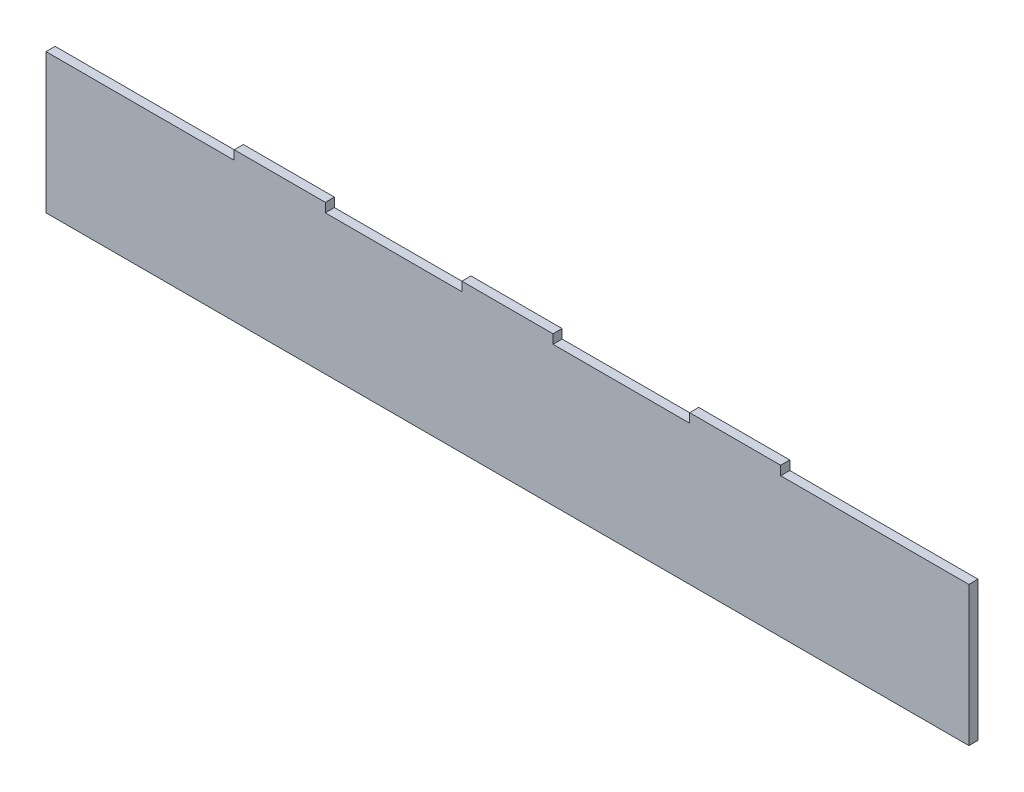
SolidWorks part; units mm, degrees
material "ABS"
ref_plane "Plan de face" through (0, 0, 0) normal (0, 0, 1) x (1, 0, 0)
ref_plane "Plan de dessus" through (0, 0, 0) normal (0, 1, 0) x (1, 0, 0)
ref_plane "Plan de droite" through (0, 0, 0) normal (1, 0, 0) x (0, 0, -1)
sketch "Esquisse1" plane through (0, 0, 0) normal (0, 0, 1) x (1, 0, 0)
  line L0 (0, 23) -> (0, -23) construction
  line L1 (152, -23) -> (-152, -23)
  line L2 (152, -23) -> (152, 23)
  line L3 (152, 23) -> (90, 23)
  line L4 (-152, -23) -> (-152, 23)
  line L5 (152, -23) -> (-152, 23) construction
  line L6 (152, 23) -> (-152, -23) construction
  line L36 (152, 23) -> (90, 23)
  line L37 (-75, 23) -> (-75, -23) construction
  line L38 (75, 23) -> (75, -23) construction
  line L39 (-90, 23) -> (-152, 23)
  line L44 (15, 23) -> (15, 26)
  line L45 (15, 26) -> (-15, 26)
  line L46 (-15, 23) -> (-15, 26)
  line L47 (15, 20) -> (-15, 26) construction
  line L48 (15, 26) -> (-15, 20) construction
  line L50 (-60, 23) -> (-60, 26)
  line L51 (-60, 26) -> (-90, 26)
  line L52 (-90, 23) -> (-90, 26)
  line L53 (-60, 20) -> (-90, 26) construction
  line L54 (-60, 26) -> (-90, 20) construction
  line L56 (90, 23) -> (90, 26)
  line L57 (90, 26) -> (60, 26)
  line L58 (60, 23) -> (60, 26)
  line L59 (90, 20) -> (60, 26) construction
  line L61 (90, 26) -> (75, 23) construction
  line L62 (-90, 23) -> (-152, 23)
  line L63 (-15, 23) -> (-60, 23)
  line L64 (0, 23) -> (-60, 23)
  line L65 (60, 23) -> (15, 23)
  line L66 (60, 23) -> (15, 23)
  point P0 (0, 0)
  dimension "D1" = 304
  dimension "D2" = 46
  dimension "D3" = 75
  dimension "D4" = 150
  dimension "D5" = 6
  dimension "D6" = 30
extrude "Boss.-Extru.1" add sketch "Esquisse1" along normal blind 3
